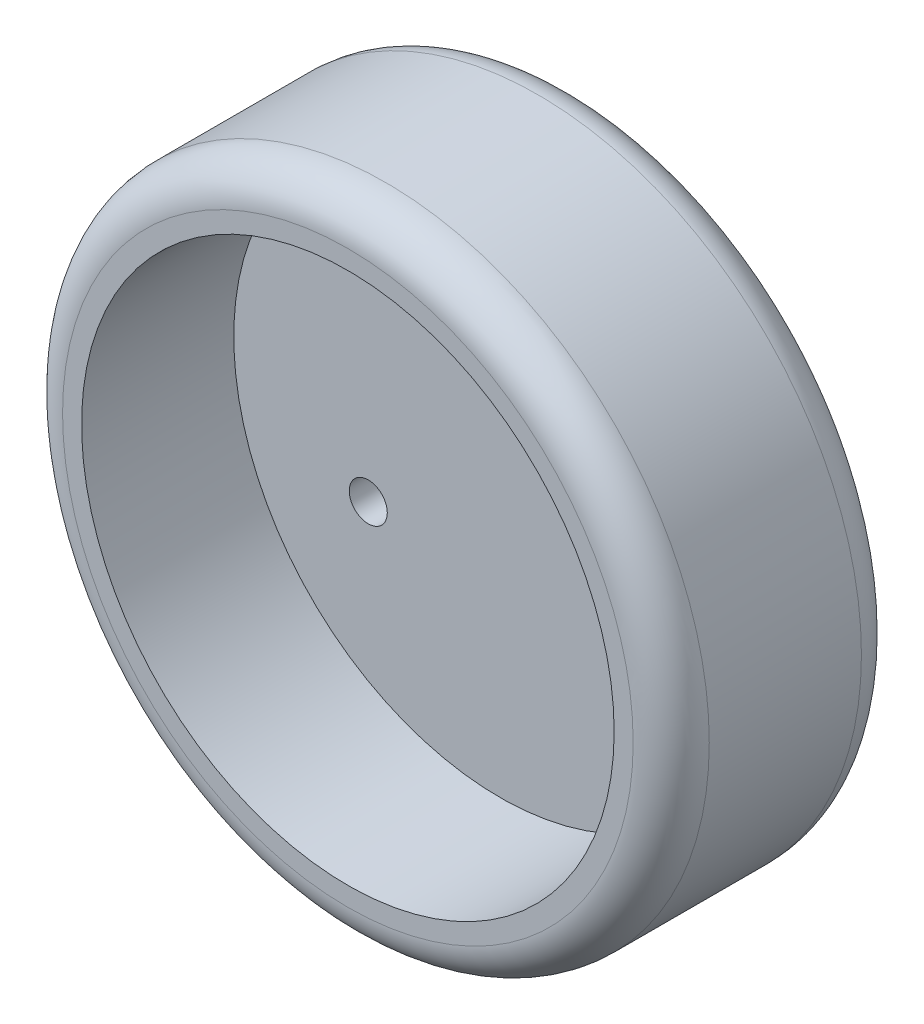
SolidWorks part; units mm, degrees
ref_plane "Front Plane" through (0, 0, 0) normal (0, 0, 1) x (1, 0, 0)
ref_plane "Top Plane" through (0, 0, 0) normal (0, 1, 0) x (1, 0, 0)
ref_plane "Right Plane" through (0, 0, 0) normal (1, 0, 0) x (0, 0, -1)
sketch "Sketch2" plane through (0, 0, 0) normal (0, 0, 1) x (1, 0, 0)
  circle A0 centre (0, 0) radius 42.5
  dimension "D1" = 85
extrude "Boss-Extrude2" add sketch "Sketch2" along normal blind 30
sketch "Sketch3" plane through (0, 0, 30) normal (0, 0, 1) x (1, 0, 0)
  circle A0 centre (0, 0) radius 42.5
  circle A1 centre (0, 0) radius 35
  dimension "D1" = 85
  dimension "D2" = 70
extrude "Cut-Extrude2" cut sketch "Sketch3" against normal blind 20 flip side to cut
sketch "Sketch8" plane through (0, 0, 10) normal (0, 0, 1) x (1, 0, 0)
  line L0 (0, 0) -> (0, 20) construction
  line L1 (0, 0) -> (17.3205, -10) construction
  line L2 (0, 0) -> (-17.3205, -10) construction
  circle A0 centre (0, 0) radius 20 construction
  circle A1 centre (0, 20) radius 2.5
  circle A2 centre (17.3205, -10) radius 2.5
  circle A3 centre (-17.3205, -10) radius 2.5
  dimension "D1" = 40
  dimension "D2" = 5
  dimension "D3" = 120
  dimension "D4" = 120
other "AlignGroup1"
extrude "Cut-Extrude3" cut sketch "Sketch8" against normal blind 10 contours A1 | A2 | A3
fillet "Fillet3" radius 5 2 edges at (42.5, 0, 0) (42.5, 0, 30)
